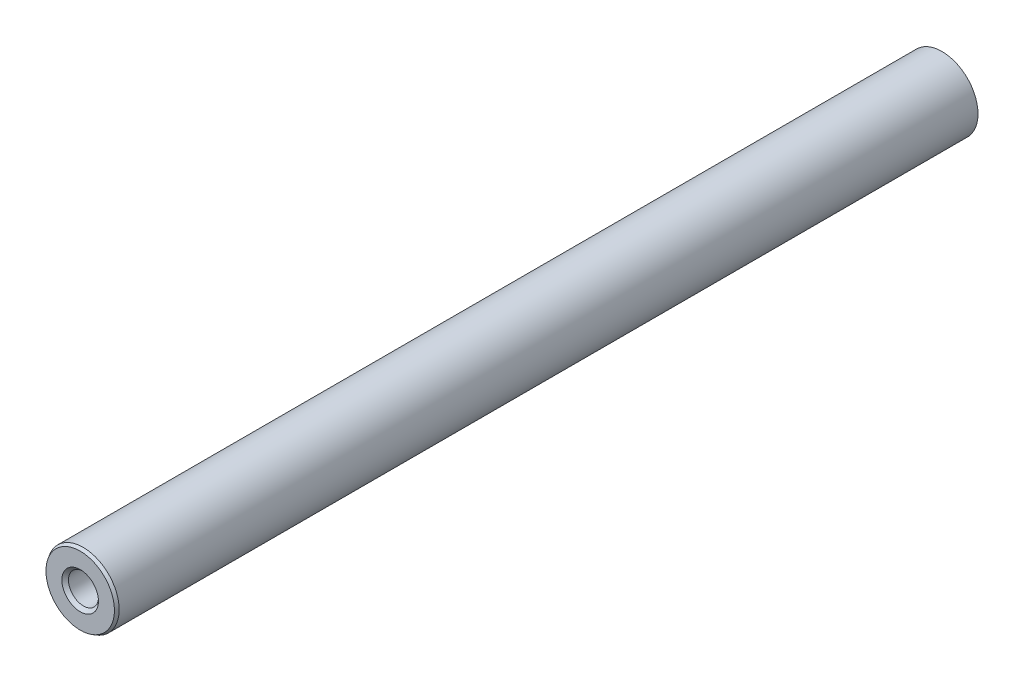
SolidWorks part; units mm, degrees
material "2018 合金"
ref_plane "正面" through (0, 0, 0) normal (0, 0, 1) x (1, 0, 0)
ref_plane "平面" through (0, 0, 0) normal (0, 1, 0) x (1, 0, 0)
ref_plane "右側面" through (0, 0, 0) normal (1, 0, 0) x (0, 0, -1)
sketch "ｽｹｯﾁ1" plane through (0, 0, 0) normal (0, 0, 1) x (1, 0, 0)
  circle A0 centre (0, 0) radius 3
  dimension "D1" = 6
extrude "ﾎﾞｽ - 押し出し1" add sketch "ｽｹｯﾁ1" along normal mid plane 72
chamfer "面取り1" distance 0.25 angle 30 2 edges at (3, 0, -36) (3, 0, 36)
hole_wizard "M3x0.5 ねじ穴1" positions "ｽｹｯﾁ2" profile "ｽｹｯﾁ3" tap size "M3x0.5" standard "JIS"
sketch "ｽｹｯﾁ2" plane through (0, 0, 36) normal (0, 0, 1) x (1, 0, 0)
  point P0 (0, 0)
sketch "ｽｹｯﾁ3" plane through (0, 0, 36) normal (1, 0, 0) x (0, -1, 0)
  line L0 (0, 0) -> (0, 13.2511)
  line L1 (0, 13.2511) -> (1.25, 12.5)
  line L2 (1.25, 12.5) -> (1.25, 0.275)
  line L3 (1.25, 0.275) -> (1.525, 0)
  line L5 (1.525, 0) -> (0, 0)
  line L6 (-1.25, 0.275) -> (-1.525, 0) construction
  line L10 (0, 13.2511) -> (-1.25, 12.5) construction
  line L11 (0, -6.35) -> (0, 107.95) construction
  dimension "ねじ下穴ﾄﾞﾘﾙ直径" = 2.5
  dimension "ねじ下穴ﾄﾞﾘﾙの深さ" = 12.5
  dimension "表面の皿穴の直径" = 3.05
  dimension "表面の皿穴の角度" = 90
  dimension "ﾄﾞﾘﾙ角度" = 118
cosmetic thread "穴のねじ山1" parameters "D1"=10, "D2"=3
mirror "ﾐﾗｰ1" about plane through (0, 0, 0) normal (0, 0, 1) of "M3x0.5 ねじ穴1"
